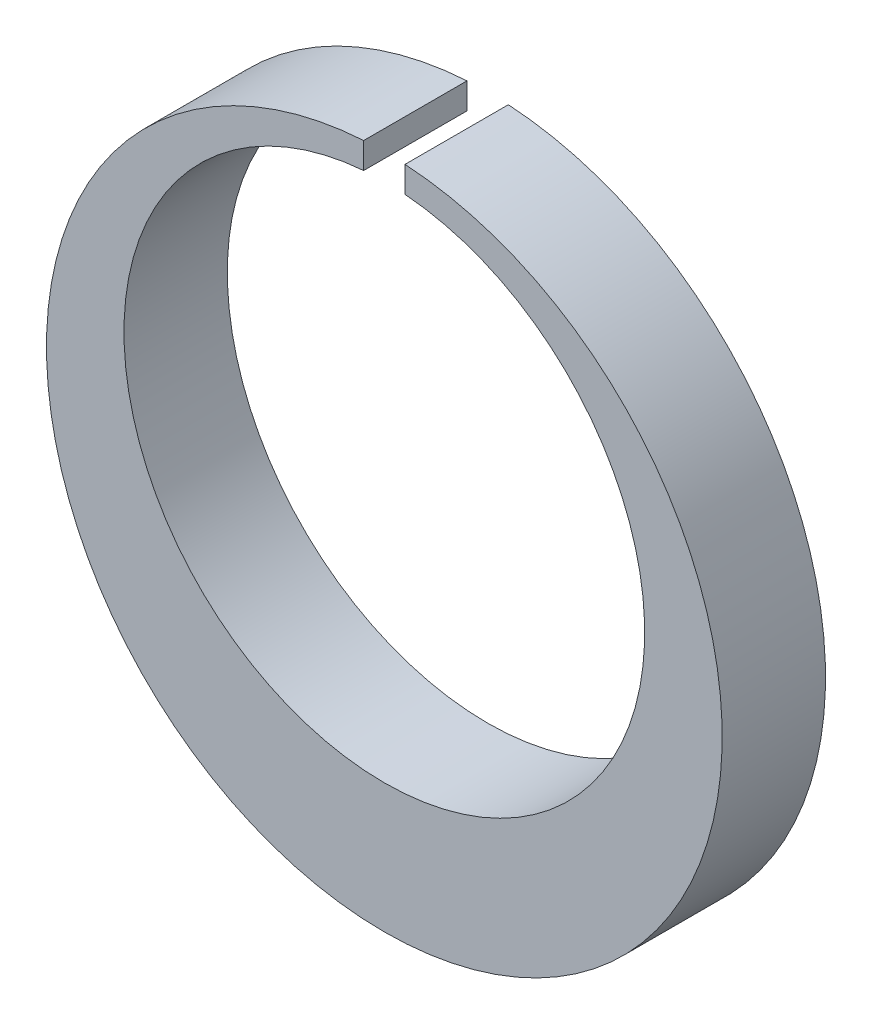
SolidWorks part; units mm, degrees
ref_plane "Front Plane" through (0, 0, 0) normal (0, 0, 1) x (1, 0, 0)
ref_plane "Top Plane" through (0, 0, 0) normal (0, 1, 0) x (1, 0, 0)
ref_plane "Right Plane" through (0, 0, 0) normal (1, 0, 0) x (0, 0, -1)
sketch "Sketch1" plane through (0, 0, 0) normal (0, 0, 1) x (1, 0, 0)
  line L0 (0, 0) -> (0, 6.35) construction
  line L1 (-2.54, 41.4513) -> (-2.54, 38.253)
  line L2 (-2.54, 31.7741) -> (2.54, 31.7741) construction
  line L3 (-2.54, 31.7741) -> (-2.54, 44.9339) construction
  line L4 (-2.54, 44.9339) -> (2.54, 44.9339) construction
  line L5 (2.54, 31.7741) -> (2.54, 44.9339) construction
  line L6 (-2.54, 31.7741) -> (2.54, 44.9339) construction
  line L7 (-2.54, 44.9339) -> (2.54, 31.7741) construction
  line L8 (2.54, 41.4513) -> (2.54, 38.253)
  circle A1 centre (0, 0) radius 41.529 construction
  arc A11 (-2.54, 41.4513) -> (2.54, 41.4513) centre (0, 0) ccw
  arc A14 (-2.54, 38.253) -> (2.54, 38.253) centre (0, 6.35) ccw
  circle A15 centre (0, 0) radius 38.354 construction
  point P0 (0, 38.354)
  point P2 (39.7144, 12.1419)
  dimension "D2" = 83.058
  dimension "D4" = 13.1598
  dimension "D10" = 3.175
  dimension "D8" = 64.008
  dimension "D3" = 5.08
extrude "Boss-Extrude1" add sketch "Sketch1" along normal blind 12.7 contours A14 L8 A11 L1
